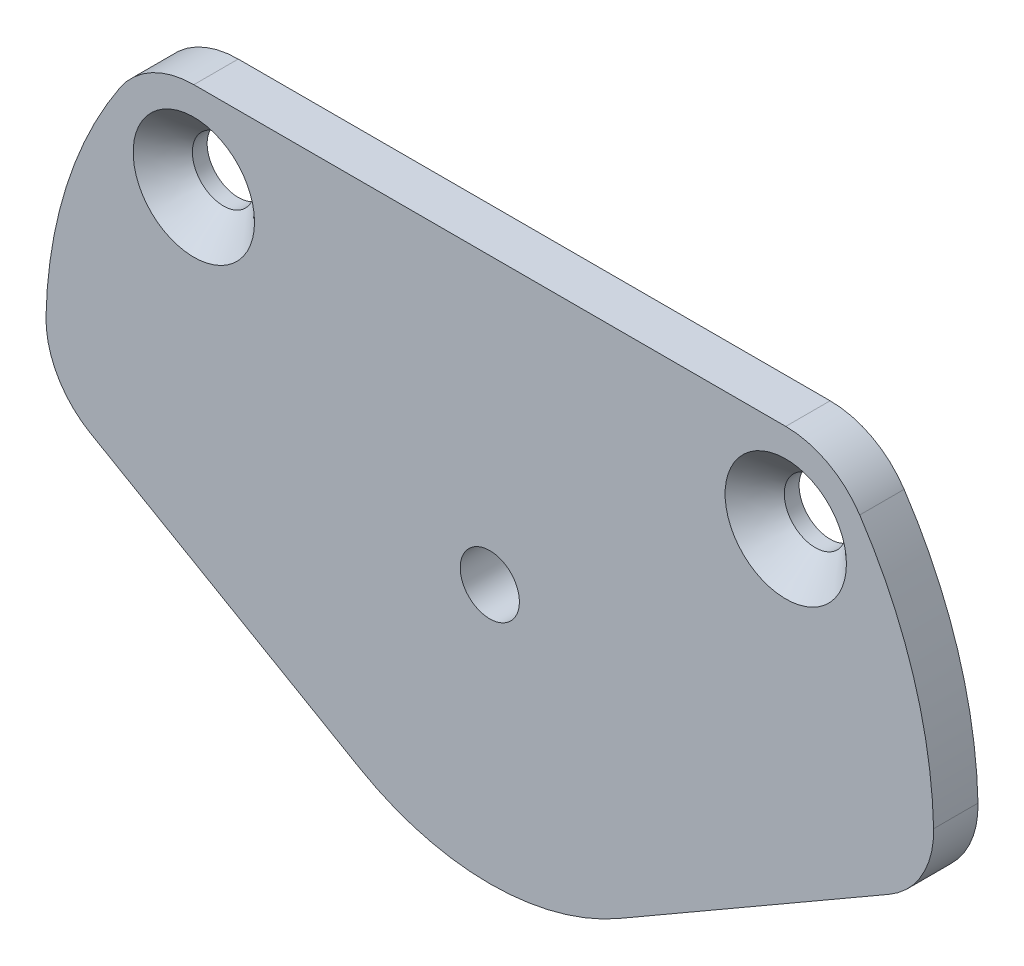
SolidWorks part; units mm, degrees
ref_plane "前视基准面" through (0, 0, 0) normal (0, 0, 1) x (1, 0, 0)
ref_plane "上视基准面" through (0, 0, 0) normal (0, 1, 0) x (1, 0, 0)
ref_plane "右视基准面" through (0, 0, 0) normal (1, 0, 0) x (0, 0, -1)
sketch "草图1" plane through (0, 0, 0) normal (0, 0, 1) x (1, 0, 0)
  line L0 (-20, 13.2665) -> (20, 13.2665) construction
  line L1 (20, 13.2665) -> (25, 16.5831) construction
  line L2 (-20, 19.2665) -> (20, 19.2665)
  line L3 (-26.9931, -4.6228) -> (-8.75, -15.1554)
  line L4 (8.75, -15.1554) -> (26.9931, -4.6228)
  circle A0 centre (-20, 13.2665) radius 2.1
  circle A1 centre (20, 13.2665) radius 2.1
  arc A2 (-25, 16.5831) -> (-29.9914, 0.7167) centre (0, 0) ccw
  arc A3 (-20, 19.2665) -> (-25, 16.5831) centre (-20, 13.2665) ccw
  arc A4 (25, 16.5831) -> (20, 19.2665) centre (20, 13.2665) ccw
  circle A5 centre (0, 0) radius 2
  arc A6 (-8.75, -15.1554) -> (8.75, -15.1554) centre (0, 0) ccw
  arc A7 (-29.9914, 0.7167) -> (-26.9931, -4.6228) centre (-23.9931, 0.5734) ccw
  arc A8 (26.9931, -4.6228) -> (29.9914, 0.7167) centre (23.9931, 0.5734) ccw
  arc A9 (29.9914, 0.7167) -> (25, 16.5831) centre (0, 0) ccw
  point P4 (0, 13.2665)
  dimension "D1" = 4.2
  dimension "D2" = 40
  dimension "D3" = 60
  dimension "D4" = 6
  dimension "D5" = 4
  dimension "D6" = 35
  dimension "D7" = 120
extrude "凸台-拉伸1" add sketch "草图1" along normal mid plane 3
chamfer "倒角1" distance 2 angle 45 2 edges at (22.1, 13.2665, 1.5) (-17.9, 13.2665, 1.5)
